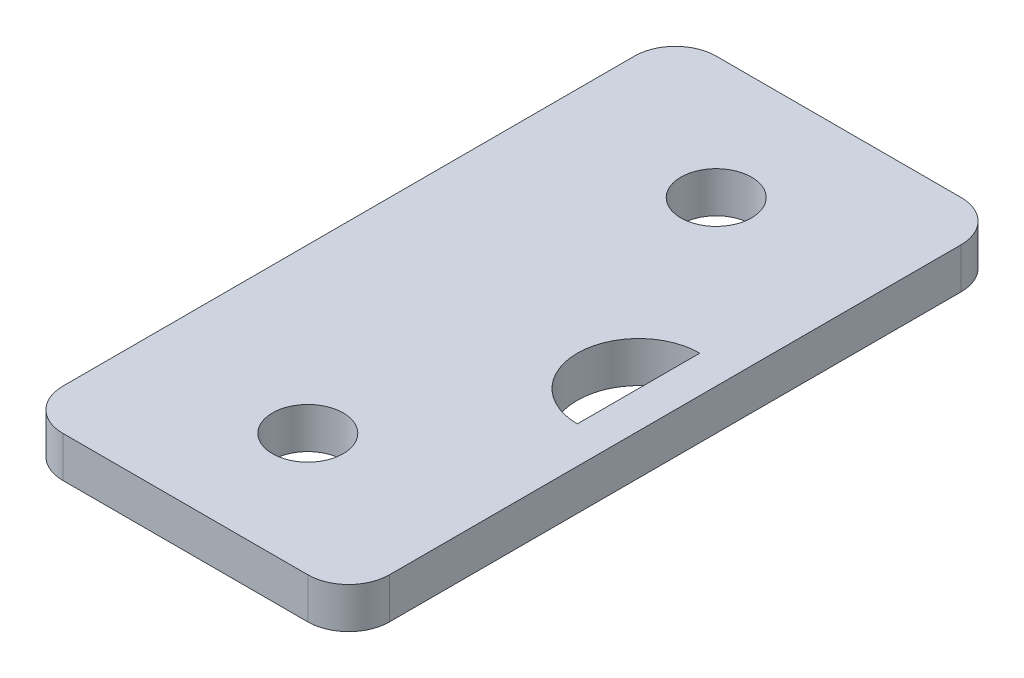
SolidWorks part; units mm, degrees
material "6061-T6 (SS)"
ref_plane "X-Y Datum" through (0, 0, 0) normal (0, 0, 1) x (1, 0, 0)
ref_plane "X-Z Datum" through (0, 0, 0) normal (0, 1, 0) x (1, 0, 0)
ref_plane "Y-Z Datum" through (0, 0, 0) normal (1, 0, 0) x (0, 0, -1)
sketch "Sketch1" plane through (0, 0, 0) normal (0, 1, 0) x (1, 0, 0)
  line L1 (-12.7, 25.4) -> (12.7, 25.4)
  line L2 (-12.7, 25.4) -> (-12.7, -25.4)
  line L3 (-12.7, -25.4) -> (12.7, -25.4)
  line L4 (12.7, 25.4) -> (12.7, -25.4)
  point P0 (0, 0)
  point P6 (-12.7, 0)
  point P7 (0, 25.4)
  dimension "D1" = 25.4
  dimension "D2" = 50.8
extrude "Boss-Extrude1" add sketch "Sketch1" along normal blind 3.175
sketch "Sketch4" plane through (0, 0, 0) normal (0, -1, 0) x (1, 0, 0)
  line L0 (-9.525, -4.7625) -> (-9.525, 4.7625)
  arc A0 (-9.525, -4.7625) -> (-9.525, 4.7625) centre (-9.525, 0) ccw
  dimension "D1" = 4.7625
  dimension "D2" = 9.525
extrude "Cut-Extrude1" [suppressed] cut sketch "Sketch4" against normal through all both and the other way through all contours A0 L0
sketch "Sketch8" plane through (0, 0, 0) normal (0, -1, 0) x (1, 0, 0)
  line L0 (9.8425, 4.7625) -> (9.8425, -4.7625)
  arc A0 (9.8425, 4.7625) -> (9.8425, -4.7625) centre (9.8425, 0) ccw
  dimension "D1" = 9.8425
  dimension "D2" = 4.7625
extrude "Cut-Extrude2" cut sketch "Sketch8" against normal through all
hole_wizard "M5 Clearance Hole1" positions "Sketch6" profile "Sketch7" hole size "M5" standard "ANSI Metric" end condition through all
sketch "Sketch6" plane through (0, 0, 0) normal (0, -1, 0) x (-1, 0, 0)
  line L1 (0, 15.875) -> (0, -15.875) construction
  point P0 (0, 15.875)
  point P2 (0, -15.875)
  point P12 (0, 0)
  dimension "D1" = 31.75
sketch "Sketch7" plane through (0, 0, -15.875) normal (1, 0, 0) x (0, 0, -1)
  line L0 (0, 0) -> (0, 3.175)
  line L1 (0, 3.175) -> (2.75, 3.175)
  line L2 (2.75, 3.175) -> (2.75, 0)
  line L5 (2.75, 0) -> (0, 0)
  line L11 (0, -6.35) -> (0, 107.95) construction
  dimension "Thru Hole Dia." = 5.5
  dimension "Thru Hole Depth" = 3.175
fillet "Fillet1" radius 3.175 4 edges at (12.7, 1.5875, -25.4) (-12.7, 1.5875, -25.4) (-12.7, 1.5875, 25.4) (12.7, 1.5875, 25.4)
